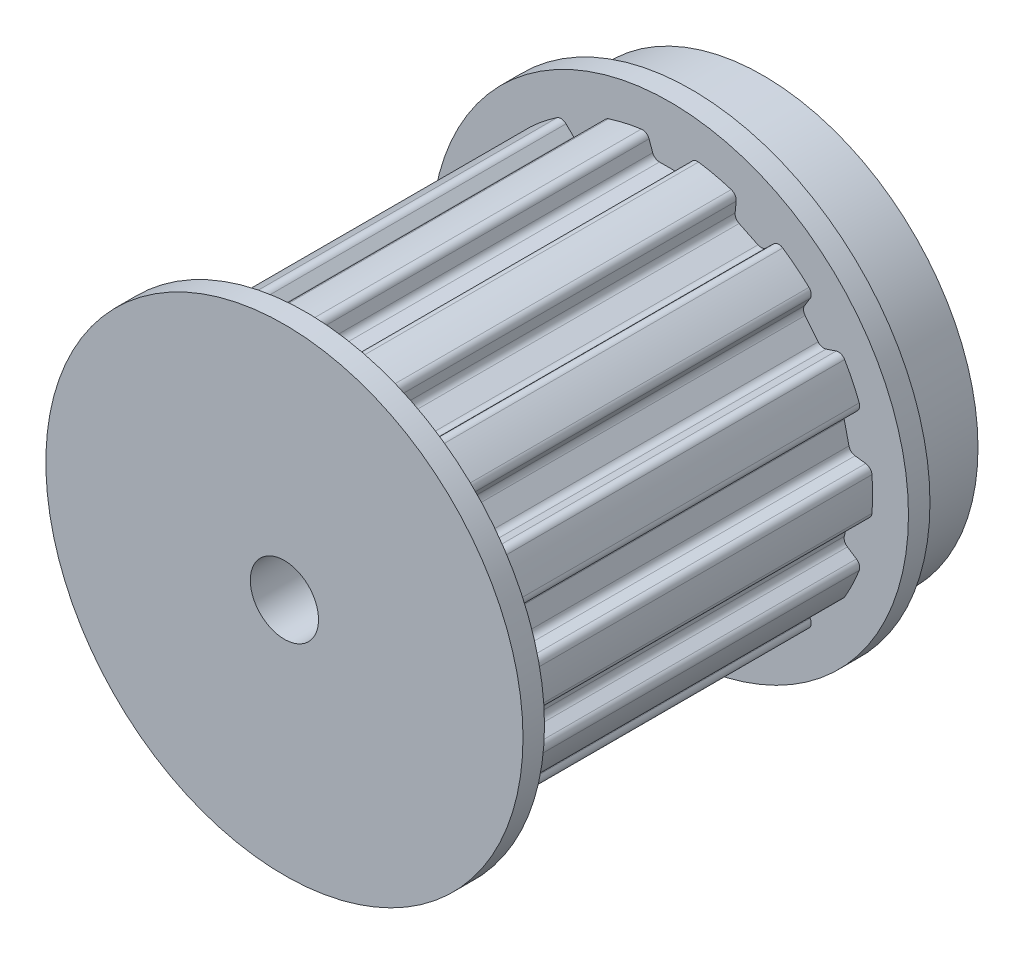
SolidWorks part; units mm, degrees
ref_plane "Front Plane" through (0, 0, 0) normal (0, 0, 1) x (1, 0, 0)
ref_plane "Top Plane" through (0, 0, 0) normal (0, 1, 0) x (1, 0, 0)
ref_plane "Right Plane" through (0, 0, 0) normal (1, 0, 0) x (0, 0, -1)
sketch "Sketch1" plane through (0, 0, 0) normal (0, 1, 0) x (1, 0, 0)
  line L0 (0, 0) -> (0, 66.8)
  line L1 (0, 66.8) -> (-30, 66.8)
  line L2 (-30, 66.8) -> (-30, 56.8)
  line L3 (-30, 56.8) -> (-33.2977, 56.8)
  line L4 (-33.2977, 56.8) -> (-33.2977, 53.8)
  line L5 (-33.2977, 53.8) -> (-28.2977, 53.8)
  line L6 (-28.2977, 53.8) -> (-28.2977, 3)
  line L7 (-28.2977, 3) -> (-33.2977, 3)
  line L8 (-33.2977, 3) -> (-33.2977, 0)
  line L9 (-33.2977, 0) -> (0, 0)
  line L10 (-33.2977, 53.8) -> (-33.2977, 3) construction
  dimension "D1" = 3
  dimension "D2" = 3
  dimension "D3" = 50.8
  dimension "D4" = 5
  dimension "D5" = 30
  dimension "D6" = 10
  dimension "D7" = 28.2977
revolve "Revolve1" add sketch "Sketch1" angle 360 about L0
sketch "Sketch2" plane through (0, 0, 0) normal (0, 0, 1) x (1, 0, 0)
  line L0 (-4.3419, 31.2977) -> (-2.1581, 25.2977)
  line L1 (-2.1581, 25.2977) -> (2.1581, 25.2977)
  line L2 (2.1581, 25.2977) -> (4.3419, 31.2977)
  line L3 (4.3419, 31.2977) -> (-4.3419, 31.2977)
  line L4 (0, 25.2977) -> (0, 0) construction
  line L5 (-3.25, 28.2977) -> (3.25, 28.2977) construction
  circle A1 centre (0, 0) radius 28.2977 construction
  dimension "D1" = 3
  dimension "D2" = 6.5
  dimension "D3" = 40
extrude "Cut-Extrude3" cut sketch "Sketch2" against normal up to surface (50.8 mm away) from offset 3 up to face at (28.2977, 0, -53.8) offset against normal yes
fillet "Fillet1" radius 1 4 edges at (2.1581, 25.2977, -28.4) (-2.1581, 25.2977, -28.4) (-3.1846, 28.118, -28.4) (3.1846, 28.118, -28.4)
pattern_circular "CirPattern1" count 14 over 360 about axis through (0, 0, 0) along (0, 0, 1) of "Fillet1", "Cut-Extrude3"
sketch "Sketch3" plane through (0, 0, -66.8) normal (0, 0, -1) x (-1, 0, 0)
  circle A0 centre (0, 0) radius 4.7625
  circle A1 centre (0, 0) radius 30 construction
  dimension "D1" = 9.525
extrude "Cut-Extrude4" cut sketch "Sketch3" against normal through all
sketch "Sketch4" plane through (0, 0, 0) normal (0, 1, 0) x (1, 0, 0)
  line L0 (0, -36.74) -> (0, 36.74) construction
  line L2 (30, 66.8) -> (-30, 66.8) construction
  circle A0 centre (0, 61.8) radius 2
  dimension "D1" = 4
  dimension "D2" = 5
extrude "Cut-Extrude5" cut sketch "Sketch4" against normal through all
sketch "Sketch6" plane through (0, 0, 0) normal (1, 0, 0) x (0, 0, -1)
  line L0 (36.74, 0) -> (-36.74, 0) construction
  line L2 (66.8, -30) -> (66.8, 30) construction
  circle A0 centre (61.8, 0) radius 2
  dimension "D1" = 5
  dimension "D2" = 4
extrude "Cut-Extrude6" cut sketch "Sketch6" against normal through all
ref_plane "Plane1" through (0, 0, -28.4) normal (0, 0, 1) x (1, 0, 0)
equation "\"teeth\"= 14"
equation "\"pitch\"= 0.5in"
equation "\"D7@Sketch1\"=\"teeth\"*\"pitch\"/(2*pi)"
equation "\"D1@CirPattern1\"=\"teeth\""
